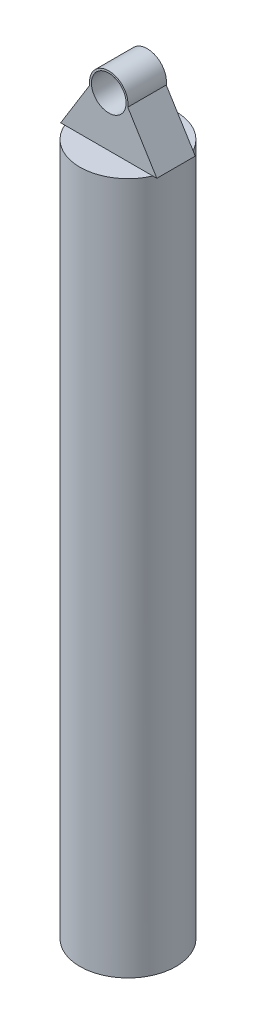
SolidWorks part; units mm, degrees
ref_plane "Front Plane" through (0, 0, 0) normal (0, 0, 1) x (1, 0, 0)
ref_plane "Top Plane" through (0, 0, 0) normal (0, 1, 0) x (1, 0, 0)
ref_plane "Right Plane" through (0, 0, 0) normal (1, 0, 0) x (0, 0, -1)
sketch "Sketch1" plane through (0, 0, 0) normal (0, 1, 0) x (1, 0, 0)
  circle A0 centre (0, 0) radius 125
  dimension "D1" = 250
extrude "Boss-Extrude1" add sketch "Sketch1" along normal blind 1400 and the other way blind 400
sketch "Sketch2" plane through (0, 0, 0) normal (0, 0, 1) x (1, 0, 0)
  line L0 (-45, 1529.5209) -> (-125, 1400)
  line L1 (45, 1529.5209) -> (125, 1400)
  line L2 (-125, 1400) -> (125, 1400)
  circle A0 centre (0, 1529.5209) radius 45
  circle A1 centre (0, 1529.5209) radius 50
  dimension "D1" = 90
  dimension "D2" = 100
extrude "Boss-Extrude2" add sketch "Sketch2" along normal mid plane 100 contours A1 L0 L2 L1 | L0 A1 L1 A0 | L1 A1 L0 A0
